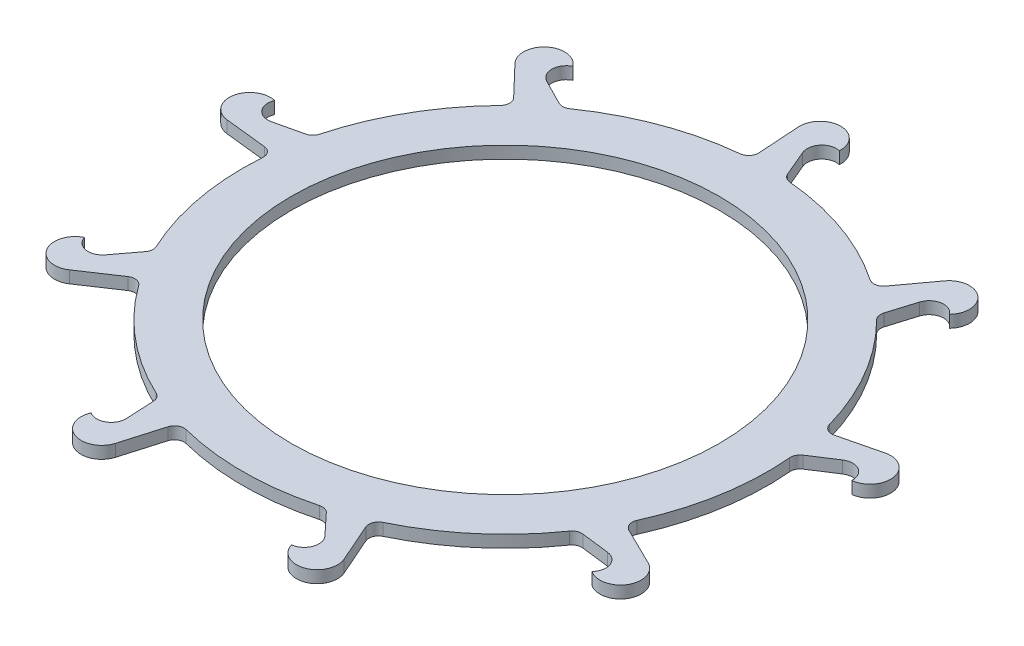
SolidWorks part; units mm, degrees
ref_plane "Front Plane" through (0, 0, 0) normal (0, 0, 1) x (1, 0, 0)
ref_plane "Top Plane" through (0, 0, 0) normal (0, 1, 0) x (1, 0, 0)
ref_plane "Right Plane" through (0, 0, 0) normal (1, 0, 0) x (0, 0, -1)
sketch "Sketch1" plane through (0, 0, 0) normal (0, 1, 0) x (1, 0, 0)
  circle A0 centre (0, 0) radius 55.9594
  circle A1 centre (0, 0) radius 68.6594
  dimension "D1" = 111.9188
  dimension "D2" = 12.7
extrude "Boss-Extrude1" add sketch "Sketch1" along normal blind 3.175
sketch "Sketch2" plane through (0, 3.175, 0) normal (0, 1, 0) x (1, 0, 0)
  line L0 (0, 0) -> (0, 135.9318) construction
  line L1 (0, 0) -> (-4.4905, 68.5124) construction
  line L2 (0, 0) -> (8.8904, 135.6408) construction
  line L3 (-4.6537, 71.0017) -> (-5.3728, 81.9729)
  line L4 (3.8894, 69.9338) -> (0.9836, 76.7774)
  line L5 (-4.6537, 71.0017) -> (-8.8904, 135.6408) construction
  arc A0 (-6.9318, 68.3086) -> (-4.6537, 71.0017) centre (-7.1883, 70.8356) ccw
  circle A1 centre (0, 0) radius 68.6594 construction
  arc A2 (5.3728, 81.9729) -> (-5.3728, 81.9729) centre (0, 82.3251) ccw
  arc A3 (5.3728, 81.9729) -> (0.9836, 76.7774) centre (4.4905, 78.2665) ccw
  arc A4 (6.0052, 68.3963) -> (-6.9318, 68.3086) centre (0, 0) ccw
  arc A5 (3.8894, 69.9338) -> (6.0052, 68.3963) centre (6.2274, 70.9265) ccw
  point P10 (4.4905, 68.5124)
  dimension "D2" = 7.62
  dimension "D3" = 19.05
  dimension "D4" = 5.3843
  dimension "D5" = 5.08
  dimension "D6" = 2.54
  dimension "D7" = 64.77
  dimension "D1" = 7.5
extrude "Boss-Extrude2" add sketch "Sketch2" against normal blind 3.175
pattern_circular "CirPattern1" count 9 over 360 about axis through (0, 0, 0) along (0, 1, 0) of "Boss-Extrude2"
sketch "Sketch4" plane through (0, 3.175, 0) normal (0, 1, 0) x (1, 0, 0)
  line L0 (0, 0) -> (0, 105.2172) construction
  line L1 (0, 0) -> (35.9864, 98.8719) construction
  line L2 (21.0579, 57.8562) -> (6.0052, 68.3963) construction
  line L3 (18.2672, 60.4622) -> (6.0052, 68.3963)
  line L4 (24.8709, 58.0587) -> (38.5978, 56.7831)
  arc A0 (38.5978, 56.7831) -> (6.0052, 68.3963) centre (0, 0) ccw construction
  arc A1 (38.5978, 56.7831) -> (6.0052, 68.3963) centre (0, 0) ccw
  arc A2 (5.3728, 81.9729) -> (-5.3728, 81.9729) centre (0, 82.3251) ccw construction
  arc A3 (5.3728, 81.9729) -> (-5.3728, 81.9729) centre (0, 82.3251) ccw construction
  arc A4 (18.2672, 60.4622) -> (24.8709, 58.0587) centre (22.9646, 63.0948) ccw
  arc A5 (3.8894, 69.9338) -> (6.0052, 68.3963) centre (6.2274, 70.9265) ccw construction
  arc A7 (3.8894, 69.9338) -> (6.0052, 68.3963) centre (6.2274, 70.9265) ccw construction
  arc A8 (38.5978, 56.7831) -> (42.0741, 57.3818) centre (40.0257, 58.8837) ccw construction
  arc A9 (38.5978, 56.7831) -> (42.0741, 57.3818) centre (40.0257, 58.8837) ccw construction
  dimension "D2" = 75
  dimension "D3" = 5.3848
  dimension "D1" = 20
  dimension "D4" = 14.605
extrude "Cut-Extrude7" [suppressed] cut sketch "Sketch4" against normal through all
pattern_circular "CirPattern12" [suppressed] count 9 over 360
sketch "Sketch5" [suppressed] plane through (0, 3.175, 0) normal (0, 1, 0) x (1, 0, 0)
  line L0 (0, 0) -> (0, 147.8799) construction
  line L1 (0, 0) -> (-11.8904, 81.7796) construction
  line L2 (0, 0) -> (11.8904, 81.7796) construction
  arc A0 (5.3728, 81.9729) -> (-5.3728, 81.9729) centre (0, 82.3251) ccw construction
  arc A1 (5.3728, 81.9729) -> (-5.3728, 81.9729) centre (0, 82.3251) ccw
  arc A2 (-3.959, 63.494) -> (3.959, 63.494) centre (0, 67.144) ccw
  circle A3 centre (0, 0) radius 67.144 construction
  arc A4 (-4.5522, 65.8457) -> (0, 69.3792) centre (0, 64.6802) cw
  arc A5 (0, 69.3792) -> (4.5522, 65.8457) centre (0, 64.6802) cw
  arc A6 (3.959, 63.494) -> (4.5522, 65.8457) centre (2.0915, 65.2157) ccw
  arc A7 (-3.959, 63.494) -> (-4.5522, 65.8457) centre (-2.0915, 65.2157) cw
  dimension "D1" = 5.3848
  dimension "D2" = 2.54
  dimension "D3" = 4.699
  dimension "D4" = 7.62
extrude "Cut-Extrude8" [suppressed] cut sketch "Sketch5" against normal through all contours A7 A2 A6 A5 A4
pattern_circular "CirPattern13" [suppressed] count 9 over 360
fillet "Fillet1" [suppressed] radius 5.08
